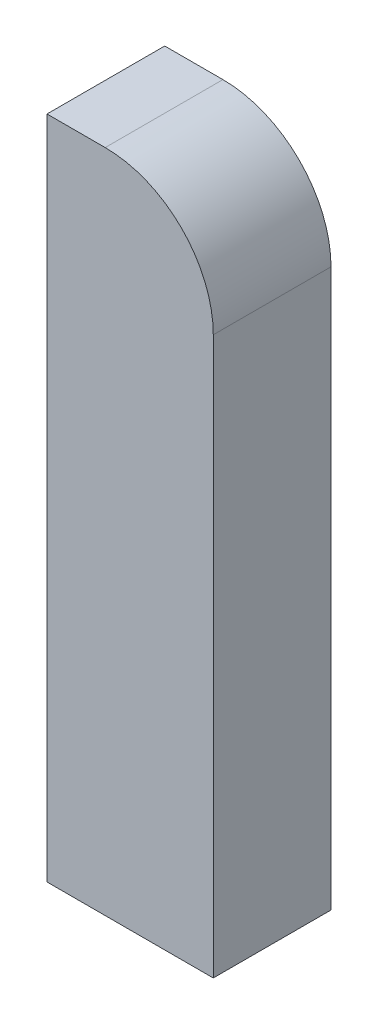
SolidWorks part; units mm, degrees
ref_plane "Front Plane" through (0, 0, 0) normal (0, 0, 1) x (1, 0, 0)
ref_plane "Top Plane" through (0, 0, 0) normal (0, 1, 0) x (1, 0, 0)
ref_plane "Right Plane" through (0, 0, 0) normal (1, 0, 0) x (0, 0, -1)
sketch "Sketch1" plane through (0, 0, 0) normal (0, 0, 1) x (1, 0, 0)
  line L1 (0, 0) -> (25.4, 0)
  line L2 (0, 0) -> (0, 101.6)
  line L3 (0, 101.6) -> (25.4, 101.6)
  line L4 (25.4, 0) -> (25.4, 101.6)
  dimension "D1" = 101.6
  dimension "D2" = 25.4
extrude "Boss-Extrude1" add sketch "Sketch1" along normal blind 17.9832
fillet "Fillet1" radius 16.51 1 edges at (25.4, 101.6, 8.9916)
